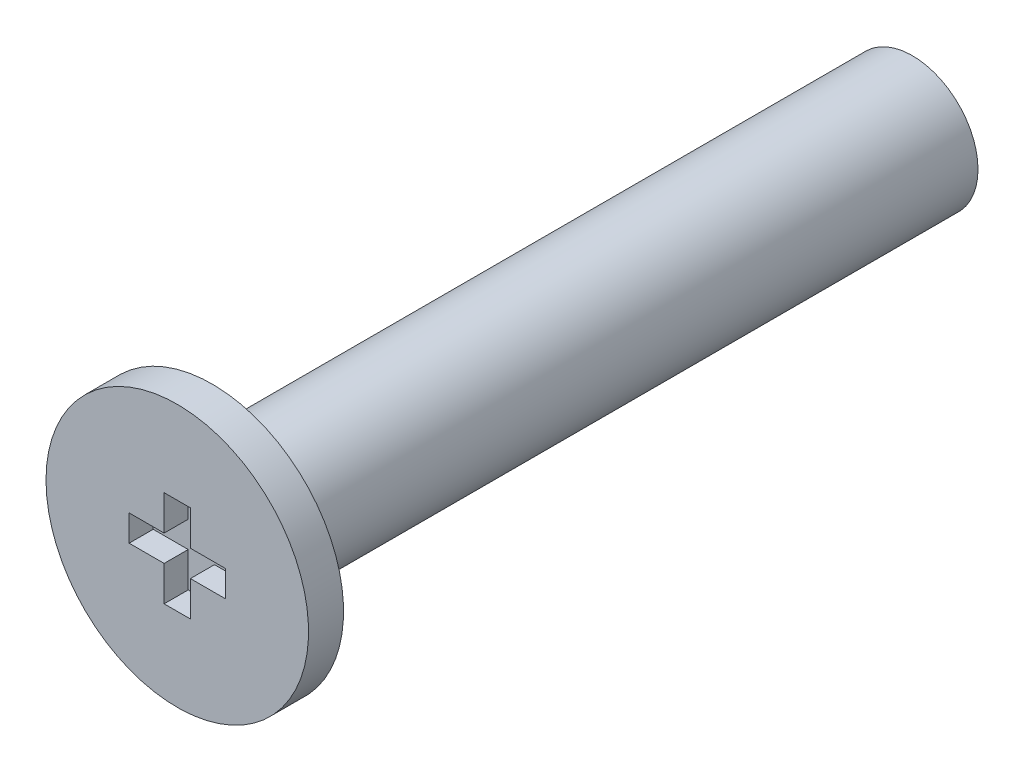
SolidWorks part; units mm, degrees
ref_plane "前视基准面" through (0, 0, 0) normal (0, 0, 1) x (1, 0, 0)
ref_plane "上视基准面" through (0, 0, 0) normal (0, 1, 0) x (1, 0, 0)
ref_plane "右视基准面" through (0, 0, 0) normal (1, 0, 0) x (0, 0, -1)
other "Configuration Table"
sketch "草图1" plane through (0, 0, 0) normal (0, 0, 1) x (1, 0, 0)
  circle A0 centre (0, 0) radius 1.5
extrude "标准杆径_头下长度" add sketch "草图1" against normal blind 16
sketch "草图2" plane through (0, 0, 0) normal (0, 0, 1) x (1, 0, 0)
  circle A0 centre (0, 0) radius 2.75
sketch "草图4" plane through (0, 0, 0) normal (0, 1, 0) x (1, 0, 0)
  line L0 (0, 0) -> (3.45, 0)
  line L1 (3.45, 0) -> (3.45, -0.3426)
  line L2 (0, -1.9) -> (0, 0)
  line L3 (0, 2) -> (0, -3.9) construction
  arc A0 (3.45, -0.3426) -> (0, -1.9) centre (0, 2.7) cw
sketch "草图5" plane through (0, 0, 0) normal (0, 0, 1) x (1, 0, 0)
  line L0 (-0.3, -1.45) -> (0.3, -1.45)
  line L1 (0.3, -1.45) -> (0.3, -0.3)
  line L2 (0.3, -0.3) -> (1.45, -0.3)
  line L3 (1.45, -0.3) -> (1.45, 0.3)
  line L4 (1.45, 0.3) -> (0.3, 0.3)
  line L5 (0.3, 0.3) -> (0.3, 1.45)
  line L6 (0.3, 1.45) -> (-0.3, 1.45)
  line L7 (-0.3, 1.45) -> (-0.3, 0.3)
  line L8 (-0.3, 0.3) -> (-1.45, 0.3)
  line L9 (-1.45, 0.3) -> (-1.45, -0.3)
  line L10 (-1.45, -0.3) -> (-0.3, -0.3)
  line L11 (-0.3, -0.3) -> (-0.3, -1.45)
sketch "草图6" plane through (0, 0, 0) normal (0, 1, 0) x (1, 0, 0)
  line L0 (0, 0) -> (3, 0)
  line L1 (3, 0) -> (3, -0.8)
  line L2 (3, -0.8) -> (0, -0.8)
  line L3 (0, -0.8) -> (0, 0)
  line L4 (0, 2) -> (0, -2.8) construction
revolve "已确认_十字槽超薄头" add sketch "草图6" angle 360 about L4
sketch "草图7" plane through (0, 0, 0) normal (0, 0, 1) x (1, 0, 0)
  line L0 (-0.3, -1.1) -> (0.3, -1.1)
  line L1 (0.3, -1.1) -> (0.3, -0.3)
  line L2 (0.3, -0.3) -> (1.1, -0.3)
  line L3 (1.1, -0.3) -> (1.1, 0.3)
  line L4 (1.1, 0.3) -> (0.3, 0.3)
  line L5 (0.3, 0.3) -> (0.3, 1.1)
  line L6 (0.3, 1.1) -> (-0.3, 1.1)
  line L7 (-0.3, 1.1) -> (-0.3, 0.3)
  line L8 (-0.3, 0.3) -> (-1.1, 0.3)
  line L9 (-1.1, 0.3) -> (-1.1, -0.3)
  line L10 (-1.1, -0.3) -> (-0.3, -0.3)
  line L11 (-0.3, -0.3) -> (-0.3, -1.1)
extrude "十字槽_PH1_简化" cut sketch "草图7" against normal blind 0.56 from offset 0.81
